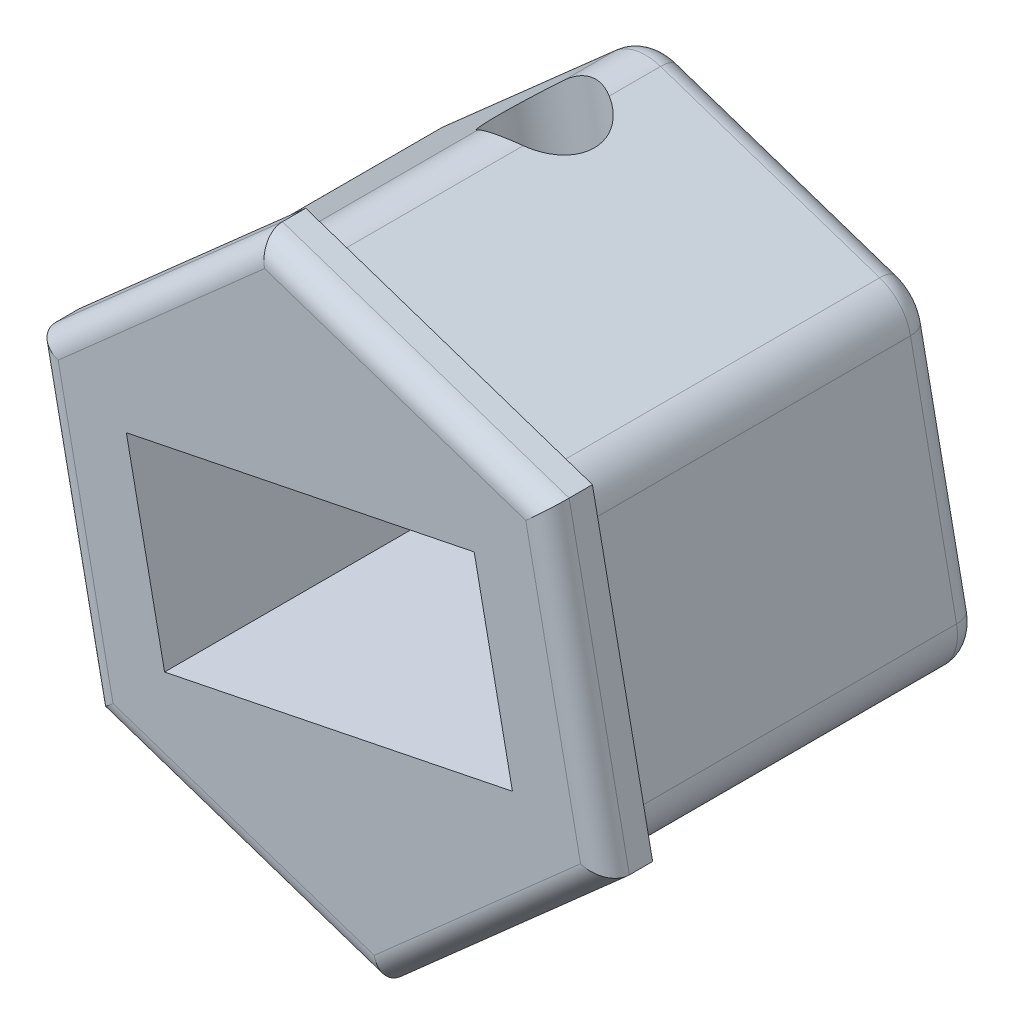
SolidWorks part; units mm, degrees
ref_plane "Płaszczyzna przednia" through (0, 0, 0) normal (0, 0, 1) x (1, 0, 0)
ref_plane "Płaszczyzna górna" through (0, 0, 0) normal (0, 1, 0) x (1, 0, 0)
ref_plane "Płaszczyzna prawa" through (0, 0, 0) normal (1, 0, 0) x (0, 0, -1)
sketch "Szkic1" plane through (0, 0, 0) normal (0, 0, 1) x (1, 0, 0)
  line L7 (1.7831, -4.5641) -> (-0.6537, 7.4307)
  line L8 (-0.6537, 7.4307) -> (-12.2599, 11.3178)
  line L9 (-12.2599, 11.3178) -> (-21.4293, 3.2101)
  line L10 (-21.4293, 3.2101) -> (-18.9925, -8.7847)
  line L11 (-18.9925, -8.7847) -> (-7.3863, -12.6718)
  line L12 (-7.3863, -12.6718) -> (1.7831, -4.5641)
  circle A0 centre (-9.8231, -0.677) radius 10.6 construction
  dimension "D1" = 21.2
extrude "Dodanie-wyciągnięcie1" add sketch "Szkic1" along normal blind 17
fillet "Zaokrąglenie1" radius 2 6 edges at (-0.6537, 7.4307, 8.5) (1.7831, -4.5641, 8.5) (-7.3863, -12.6718, 8.5) (-18.9925, -8.7847, 8.5) (-21.4293, 3.2101, 8.5) (-12.2599, 11.3178, 8.5)
sketch "Szkic3" plane through (0, 0, 17) normal (0, 0, 1) x (1, 0, 0)
  line L0 (-21.1995, 2.0785) -> (1.5532, -3.4325) construction
  line L1 (-13.125, 10.5529) -> (-6.5213, -11.9069) construction
  line L2 (1.5532, -3.4325) -> (-0.4238, 6.2991) construction
  line L3 (-0.0915, 7.9279) -> (-12.4094, 12.0533)
  line L4 (-12.4094, 12.0533) -> (-22.141, 3.4484)
  line L5 (-22.141, 3.4484) -> (-19.5548, -9.2819)
  line L6 (-19.5548, -9.2819) -> (-7.2369, -13.4074)
  line L7 (-7.2369, -13.4074) -> (2.4948, -4.8025)
  line L8 (2.4948, -4.8025) -> (-0.0915, 7.9279)
  circle A0 centre (-9.8231, -0.677) radius 11.25 construction
  dimension "D1" = 0
  dimension "D2" = 22.5
extrude "Dodanie-wyciągnięcie2" add sketch "Szkic3" against normal blind 2
fillet "Zaokrąglenie2" radius 1 12 edges at (-0.8855, 7.2258, 0) (0.5647, 1.4333, 0) (1.4897, -4.4658, 0) (-2.8016, -8.618, 0) (-7.4479, -12.3686, 0) (-13.1894, -10.7283, 0) (-18.7608, -8.5798, 0) (-20.2109, -2.7873, 0) (-21.136, 3.1118, 0) (-16.8446, 7.2639, 0) (-12.1983, 11.0146, 0) (-6.4568, 9.3743, 0)
ref_plane "Płaszczyzna1" through (-9.5659, -1.9433, 0) normal (0.98, 0.1991, 0) x (0, 0, -1)
ref_plane "Płaszczyzna2" through (-0.2573, 1.2663, 0) normal (-0.1991, 0.98, 0) x (0.98, 0.1991, 0)
fillet "Zaokrąglenie3" radius 1 6 edges at (-2.3711, -9.1049, 17) (-13.3959, -11.3446, 17) (-20.8479, -2.9168, 17) (-17.2752, 7.7509, 17) (-6.2504, 9.9906, 17) (1.2017, 1.5627, 17)
sketch "Szkic4" plane through (-0.2573, 1.2663, 0) normal (-0.1991, 0.98, 0) x (0.98, 0.1991, 0)
  line L0 (-9.7613, -10.9512) -> (-9.7613, 10.9512) construction
  line L2 (1.4887, -15) -> (-9.7613, -15) construction
  circle A0 centre (-9.7613, -5.05) radius 2.1
  dimension "D1" = 0
  dimension "D3" = 4.2
  dimension "D2" = 9.95
extrude "Wytnij-wyciągnięcie1" cut sketch "Szkic4" against normal through all both and the other way through all
sketch "Szkic5" plane through (0, 0, 17) normal (0, 0, 1) x (1, 0, 0)
  line L0 (-18.1167, 1.8474) -> (-3.172, 4.8834)
  line L1 (-16.4743, -6.2375) -> (-1.5295, -3.2014)
  line L5 (-1.5295, -3.2014) -> (-3.172, 4.8834)
  line L8 (-7.3856, -12.6753) -> (-11.7461, 8.7886) construction
  line L9 (-16.4743, -6.2375) -> (-18.1167, 1.8474)
extrude "Wytnij-wyciągnięcie2" cut sketch "Szkic5" against normal through all
sketch "Szkic6" plane through (-1.0785, 5.3088, 0) normal (0.1991, -0.98, 0) x (0.98, 0.1991, 0)
  circle A0 centre (-9.7613, 5.05) radius 2.1
  circle A1 centre (-9.7613, 5.05) radius 1.25
extrude "Dodanie-wyciągnięcie3" add sketch "Szkic6" against normal blind 0.51
mirror "Lustro1" about plane through (-0.2573, 1.2663, 0) normal (-0.1991, 0.98, 0) of "Dodanie-wyciągnięcie3"
